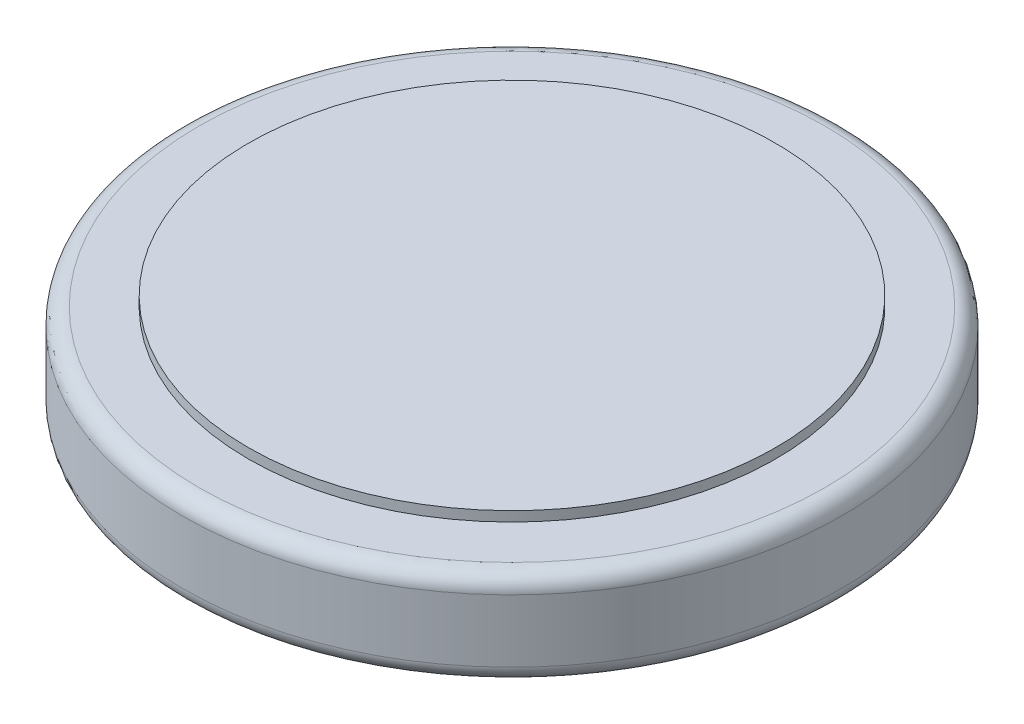
SolidWorks part; units mm, degrees
material "Nickel"
ref_plane "Front Plane" through (0, 0, 0) normal (0, 0, 1) x (1, 0, 0)
ref_plane "Top Plane" through (0, 0, 0) normal (0, 1, 0) x (1, 0, 0)
ref_plane "Right Plane" through (0, 0, 0) normal (1, 0, 0) x (0, 0, -1)
sketch "Sketch1" plane through (0, 0, 0) normal (0, 1, 0) x (1, 0, 0)
  circle A0 centre (0, 0) radius 10
  dimension "D1" = 20
extrude "Boss-Extrude1" add sketch "Sketch1" along normal blind 2.9 contours A0
sketch "Sketch2" plane through (0, 2.9, 0) normal (0, 1, 0) x (1, 0, 0)
  circle A0 centre (0, 0) radius 8
  dimension "D1" = 16
extrude "Boss-Extrude2" add sketch "Sketch2" along normal blind 0.3
fillet "Fillet1" radius 0.5 2 edges at (0, 0, 10) (0, 2.9, 10)
